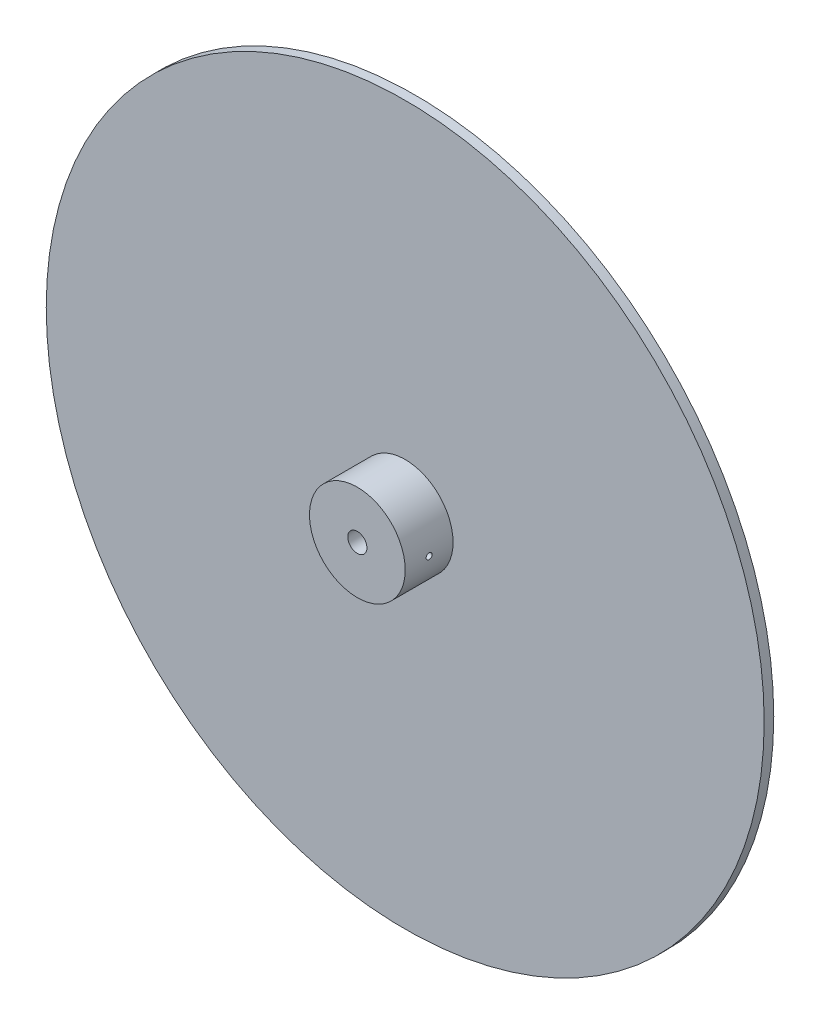
SolidWorks part; units mm, degrees
ref_plane "Front Plane" through (0, 0, 0) normal (0, 0, 1) x (1, 0, 0)
ref_plane "Top Plane" through (0, 0, 0) normal (0, 1, 0) x (1, 0, 0)
ref_plane "Right Plane" through (0, 0, 0) normal (1, 0, 0) x (0, 0, -1)
sketch "Sketch1" plane through (0, 0, 0) normal (0, 0, 1) x (1, 0, 0)
  circle A0 centre (0, 0) radius 150
extrude "Disc" add sketch "Sketch1" along normal blind 4
ref_plane "Plane_z4" through (0, 0, 4) normal (0, 0, 1) x (1, 0, 0)
sketch "Sketch2" plane through (0, 0, 4) normal (0, 0, 1) x (1, 0, 0)
  circle A0 centre (0, 0) radius 20
extrude "Hub" add sketch "Sketch2" along normal blind 20
sketch "Sketch3" plane through (0, 0, 0) normal (0, 0, 1) x (1, 0, 0)
  circle A0 centre (0, 0) radius 4
extrude "Bore" cut sketch "Sketch3" along normal blind 24
sketch "Sketch4" plane through (0, 0, 0) normal (0, 0, 1) x (1, 0, 0)
  line L0 (27.3244, -97.9181) -> (99.1067, -97.9181)
  line L1 (99.1067, -97.9181) -> (99.1067, -94.9181)
  line L2 (99.1067, -94.9181) -> (27.3244, -94.9181)
  line L3 (27.3244, -94.9181) -> (27.3244, -97.9181)
  line L4 (83.8722, -57.4459) -> (138.8607, -11.3051)
  line L5 (138.8607, -11.3051) -> (136.9323, -9.007)
  line L6 (136.9323, -9.007) -> (81.9439, -55.1478)
  line L7 (81.9439, -55.1478) -> (83.8722, -57.4459)
  line L8 (101.1754, 9.9059) -> (113.6402, 80.5977)
  line L9 (113.6402, 80.5977) -> (110.6858, 81.1187)
  line L10 (110.6858, 81.1187) -> (98.2209, 10.4269)
  line L11 (98.2209, 10.4269) -> (101.1754, 9.9059)
  line L12 (71.1374, 72.6227) -> (35.2463, 134.788)
  line L13 (35.2463, 134.788) -> (32.6482, 133.288)
  line L14 (32.6482, 133.288) -> (68.5393, 71.1227)
  line L15 (68.5393, 71.1227) -> (71.1374, 72.6227)
  line L16 (7.8135, 101.3584) -> (-59.6398, 125.9094)
  line L17 (-59.6398, 125.9094) -> (-60.6659, 123.0904)
  line L18 (-60.6659, 123.0904) -> (6.7874, 98.5394)
  line L19 (6.7874, 98.5394) -> (7.8135, 101.3584)
  line L20 (-59.1665, 82.6675) -> (-126.6198, 58.1165)
  line L21 (-126.6198, 58.1165) -> (-125.5937, 55.2974)
  line L22 (-125.5937, 55.2974) -> (-58.1404, 79.8484)
  line L23 (-58.1404, 79.8484) -> (-59.1665, 82.6675)
  line L24 (-98.4618, 25.2955) -> (-134.3529, -36.8698)
  line L25 (-134.3529, -36.8698) -> (-131.7549, -38.3698)
  line L26 (-131.7549, -38.3698) -> (-95.8637, 23.7955)
  line L27 (-95.8637, 23.7955) -> (-98.4618, 25.2955)
  line L28 (-91.6857, -43.9126) -> (-79.2209, -114.6043)
  line L29 (-79.2209, -114.6043) -> (-76.2664, -114.0834)
  line L30 (-76.2664, -114.0834) -> (-88.7313, -43.3916)
  line L31 (-88.7313, -43.3916) -> (-91.6857, -43.9126)
  line L32 (-42.0089, -92.5734) -> (12.9795, -138.7142)
  line L33 (12.9795, -138.7142) -> (14.9079, -136.4161)
  line L34 (14.9079, -136.4161) -> (-40.0805, -90.2753)
  line L35 (-40.0805, -90.2753) -> (-42.0089, -92.5734)
extrude "Blade_slots" cut sketch "Sketch4" along normal blind 3
ref_plane "Plane_x3_5" through (3.5, 0, 0) normal (1, 0, 0) x (0, 0, -1)
sketch "Sketch5" plane through (3.5, 0, 0) normal (1, 0, 0) x (0, 0, -1)
  circle A0 centre (-14, 0) radius 1.25
extrude "Clamp_screw" cut sketch "Sketch5" along normal blind 17
